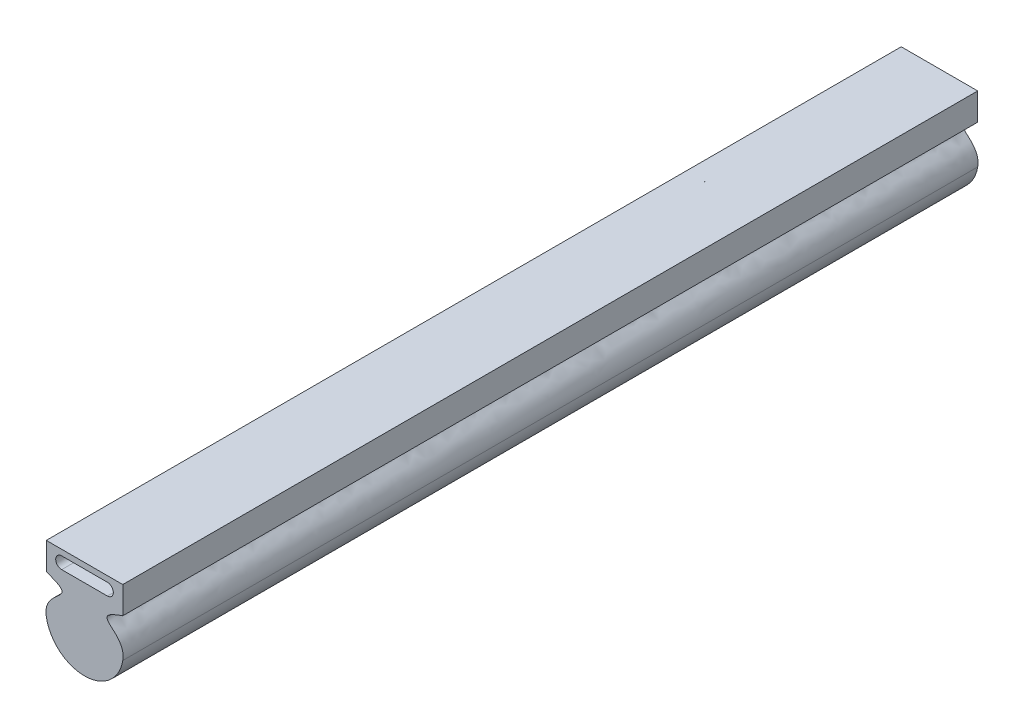
SolidWorks part; units mm, degrees
ref_plane "Plan de face" through (0, 0, 0) normal (0, 0, 1) x (1, 0, 0)
ref_plane "Plan de dessus" through (0, 0, 0) normal (0, 1, 0) x (1, 0, 0)
ref_plane "Plan de droite" through (0, 0, 0) normal (1, 0, 0) x (0, 0, -1)
sketch "Esquisse1" plane through (0, 0, 0) normal (0, 0, 1) x (1, 0, 0)
  line L0 (-14, 0) -> (14, 0)
  line L1 (14, 0) -> (14, -9.9133)
  line L2 (0, 0) -> (0, 37.0156) construction
  line L3 (-14, 0) -> (-14, -9.9133)
  line L4 (-8.3672, -4.2772) -> (8.3672, -4.2772) construction
  line L5 (-8.3672, -2.0973) -> (8.3672, -2.0973)
  line L6 (-8.3672, -6.4571) -> (8.3672, -6.4571)
  arc A0 (-14, -24.1011) -> (14, -24.1011) centre (0, -21.8145) ccw
  arc A1 (-8.3672, -2.0973) -> (-8.3672, -6.4571) centre (-8.3672, -4.2772) ccw
  arc A2 (8.3672, -6.4571) -> (8.3672, -2.0973) centre (8.3672, -4.2772) ccw
  spline S0 degree 3 poles (14, -9.9133) (0.2785, -14.5535) (15.5503, -14.6091) (14, -24.1011) knots 0 0 0 0 1 1 1 1
  spline S1 degree 3 poles (-14, -9.9133) (-0.2785, -14.5535) (-15.5503, -14.6091) (-14, -24.1011) knots 0 0 0 0 1 1 1 1
  point P4 (0, 0)
  point P16 (0, -4.2772)
  dimension "D1" = 28
extrude "Boss.-Extru.1" add sketch "Esquisse1" along normal blind 313
